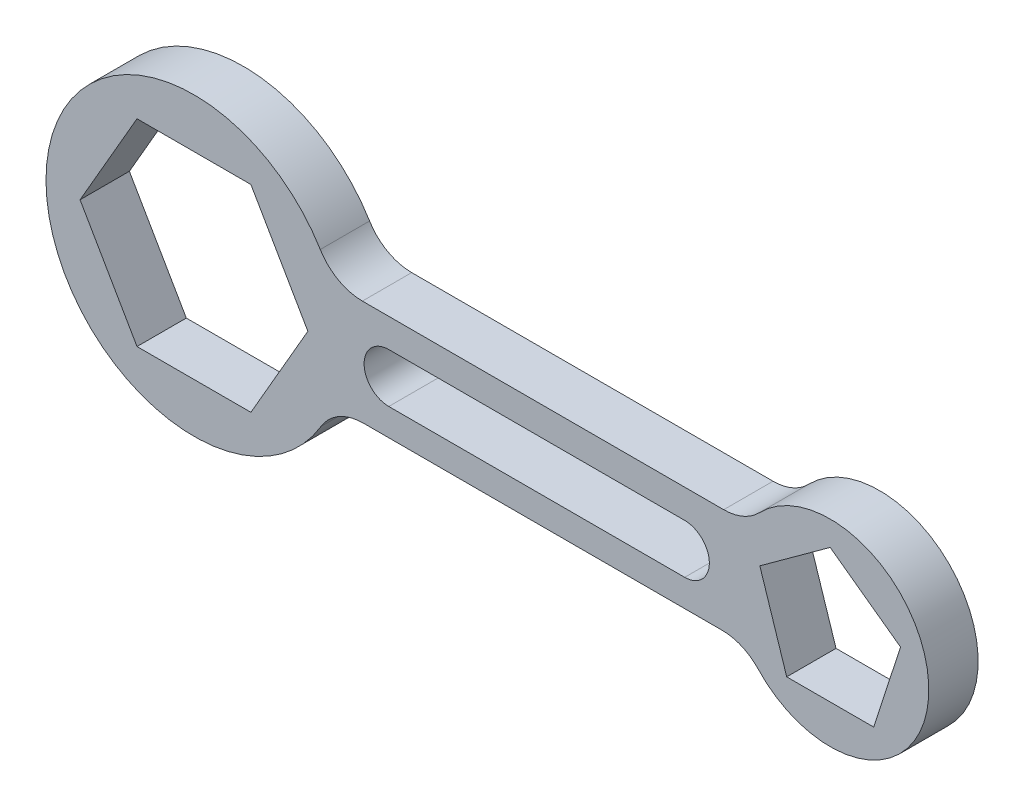
SolidWorks part; units mm, degrees
ref_plane "Front Plane" through (0, 0, 0) normal (0, 0, 1) x (1, 0, 0)
ref_plane "Top Plane" through (0, 0, 0) normal (0, 1, 0) x (1, 0, 0)
ref_plane "Right Plane" through (0, 0, 0) normal (1, 0, 0) x (0, 0, -1)
sketch "Sketch1" plane through (0, 0, 0) normal (0, 0, 1) x (1, 0, 0)
  line L0 (39.5, 0) -> (99.5, 0) construction
  line L8 (11.547, 20) -> (-11.547, 20)
  line L9 (-11.547, 20) -> (-23.094, 0)
  line L10 (-23.094, 0) -> (-11.547, -20)
  line L11 (-11.547, -20) -> (11.547, -20)
  line L12 (11.547, -20) -> (23.094, 0)
  line L13 (23.094, 0) -> (11.547, 20)
  line L14 (129, 15) -> (114.7342, 4.6353)
  line L15 (114.7342, 4.6353) -> (120.1832, -12.1353)
  line L16 (120.1832, -12.1353) -> (137.8168, -12.1353)
  line L17 (137.8168, -12.1353) -> (143.2658, 4.6353)
  line L18 (143.2658, 4.6353) -> (129, 15)
  line L19 (34.1482, 10.8303) -> (107.4107, 10.8303)
  line L20 (34.3467, -10.5013) -> (107.098, -10.5013)
  line L23 (39.5, 5) -> (99.5, 5)
  line L24 (39.5, -5) -> (99.5, -5)
  arc A0 (25.6112, 15.6227) -> (25.76, -15.376) centre (0, 0) ccw
  arc A1 (114.3987, -13.6675) -> (114.6071, 13.8868) centre (129, 0) ccw
  circle A2 centre (0, 0) radius 20 construction
  circle A3 centre (129, 0) radius 12.1353 construction
  arc A6 (39.5, 5) -> (39.5, -5) centre (39.5, 0) ccw
  arc A7 (99.5, -5) -> (99.5, 5) centre (99.5, 0) ccw
  arc A8 (34.1482, 10.8303) -> (25.6112, 15.6227) centre (34.1482, 20.8303) cw
  arc A9 (34.3467, -10.5013) -> (25.76, -15.376) centre (34.3467, -20.5013) ccw
  arc A10 (107.4107, 10.8303) -> (114.6071, 13.8868) centre (107.4107, 20.8303) ccw
  arc A11 (114.3987, -13.6675) -> (107.098, -10.5013) centre (107.098, -20.5013) ccw
  point P19 (0, -11.805)
  point P25 (69.5, 0)
  dimension "D1" = 60
  dimension "D3" = 40
  dimension "D7" = 10
  dimension "D6" = 10
  dimension "D8" = 10
  dimension "D9" = 10
  dimension "D2" = 129
  dimension "D4" = 20
  dimension "D5" = 15
extrude "Boss-Extrude1" add sketch "Sketch1" along normal blind 10
